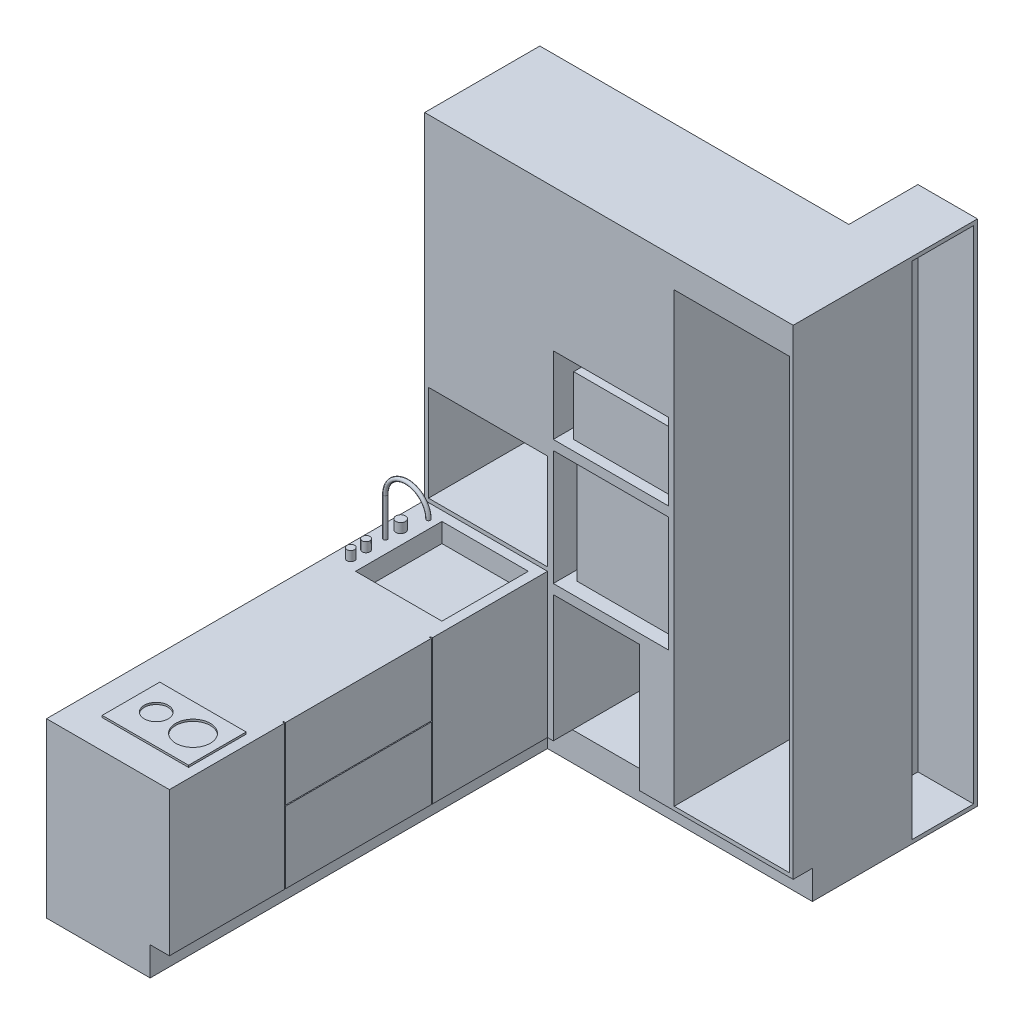
SolidWorks part; units mm, degrees
ref_plane "Спереди" through (0, 0, 0) normal (0, 0, 1) x (1, 0, 0)
ref_plane "Сверху" through (0, 0, 0) normal (0, 1, 0) x (1, 0, 0)
ref_plane "Справа" through (0, 0, 0) normal (1, 0, 0) x (0, 0, -1)
sketch "Эскиз1" plane through (0, 0, 0) normal (0, 1, 0) x (1, 0, 0)
  line L0 (-310, 0) -> (-1920, 0)
  line L1 (-1920, 0) -> (-1920, -2570)
  line L2 (-1920, -2570) -> (-1280, -2570)
  line L3 (-1280, -2570) -> (-1280, -600)
  line L4 (-1280, -600) -> (0, -600)
  line L5 (0, -600) -> (0, 0)
  line L6 (0, 0) -> (0, 360)
  line L7 (0, 360) -> (-310, 360)
  line L8 (-310, 360) -> (-310, 0)
  line L9 (0, 0) -> (-310, 0) construction
  dimension "D1" = 1610
  dimension "D2" = 2570
  dimension "D3" = 640
  dimension "D4" = 600
  dimension "D5" = 310
  dimension "D6" = 360
extrude "Бобышка-Вытянуть1" add sketch "Эскиз1" along normal blind 900
sketch "Эскиз2" plane through (0, 900, 0) normal (0, 1, 0) x (1, 0, 0)
  line L0 (-1920, 0) -> (-310, 0)
  line L1 (-310, 0) -> (-310, 360)
  line L2 (-310, 360) -> (0, 360)
  line L3 (0, 360) -> (0, -600)
  line L4 (0, -600) -> (-1920, -600)
  line L5 (-1920, 0) -> (-1920, -2570) construction
  line L6 (-1920, -600) -> (-1920, 0)
extrude "Бобышка-Вытянуть2" add sketch "Эскиз2" along normal blind 1750
sketch "Эскиз4" plane through (0, 0, 0) normal (0, -1, 0) x (-1, 0, 0)
  line L0 (1280, -2570) -> (1380, -2570)
  line L1 (1920, -2570) -> (1280, -2570) construction
  line L2 (1380, -2570) -> (1380, -500)
  line L3 (1380, -500) -> (0, -500)
  line L4 (0, -600) -> (0, 360) construction
  line L5 (0, -500) -> (0, -600)
  line L6 (0, -600) -> (1280, -600)
  line L7 (1280, -600) -> (1280, -2570)
  dimension "D1" = 100
extrude "Вырез-Вытянуть1" cut sketch "Эскиз4" against normal blind 150
sketch "Эскиз5" plane through (0, 0, 600) normal (0, 0, 1) x (1, 0, 0)
  line L0 (0, 150) -> (-1280, 150) construction
  line L1 (-620, 2500) -> (-20, 2500)
  line L2 (-620, 2500) -> (-620, 170)
  line L3 (-620, 170) -> (-20, 170)
  line L4 (-20, 2500) -> (-20, 170)
  line L5 (0, 2650) -> (0, 150) construction
  line L6 (-1920, 2650) -> (0, 2650) construction
  dimension "D1" = 20
  dimension "D2" = 20
  dimension "D3" = 150
  dimension "D4" = 600
extrude "Вырез-Вытянуть3" cut sketch "Эскиз5" against normal up to surface (600 mm away) up to face at (-1115, 1325, 0)
sketch "Эскиз6" plane through (0, 0, 600) normal (0, 0, 1) x (1, 0, 0)
  line L0 (-1380, 150) -> (0, 150) construction
  line L1 (-1250, 810) -> (-800, 810)
  line L2 (-1250, 810) -> (-1250, 150)
  line L3 (-1250, 150) -> (-800, 150)
  line L4 (-800, 810) -> (-800, 150)
  line L5 (-1280, 900) -> (-1280, 150) construction
  dimension "D1" = 450
  dimension "D2" = 660
  dimension "D3" = 30
extrude "Вырез-Вытянуть4" cut sketch "Эскиз6" against normal up to surface (600 mm away) up to face at (-790, 1330, 0)
sketch "Эскиз7" plane through (0, 0, 600) normal (0, 0, 1) x (1, 0, 0)
  line L0 (-1280, 900) -> (-1280, 150) construction
  line L1 (-1250, 1460) -> (-650, 1460)
  line L2 (-1250, 1460) -> (-1250, 860)
  line L3 (-1250, 860) -> (-650, 860)
  line L4 (-650, 1460) -> (-650, 860)
  line L5 (-800, 810) -> (-1250, 810) construction
  dimension "D1" = 600
  dimension "D2" = 600
  dimension "D3" = 30
  dimension "D4" = 50
extrude "Вырез-Вытянуть5" cut sketch "Эскиз7" against normal up to surface (600 mm away) up to face at (-1025, 480, 0)
sketch "Эскиз8" plane through (0, 0, 600) normal (0, 0, 1) x (1, 0, 0)
  line L0 (-1280, 900) -> (-1280, 150) construction
  line L1 (-1250, 1910) -> (-650, 1910)
  line L2 (-1250, 1910) -> (-1250, 1510)
  line L3 (-1250, 1510) -> (-650, 1510)
  line L4 (-650, 1910) -> (-650, 1510)
  line L5 (-650, 1460) -> (-1250, 1460) construction
  dimension "D1" = 600
  dimension "D2" = 400
  dimension "D3" = 30
  dimension "D4" = 50
extrude "Вырез-Вытянуть6" cut sketch "Эскиз8" against normal up to surface (600 mm away) up to face at (-950, 1160, 0)
sketch "Эскиз9" plane through (0, 0, 0) normal (1, 0, 0) x (0, 0, -1)
  line L0 (360, 2650) -> (360, 0) construction
  line L1 (340, 2630) -> (20, 2630)
  line L2 (340, 2630) -> (340, 20)
  line L3 (340, 20) -> (20, 20)
  line L4 (20, 2630) -> (20, 20)
  line L5 (-500, 0) -> (360, 0) construction
  line L6 (-600, 2650) -> (360, 2650) construction
  line L7 (0, 2500) -> (0, 170) construction
  dimension "D1" = 20
  dimension "D2" = 20
  dimension "D3" = 20
  dimension "D4" = 20
extrude "Вырез-Вытянуть7" cut sketch "Эскиз9" against normal offset from surface (290 mm away) 20 up to face at (-310, 1328.3333, -120)
sketch "Эскиз10" plane through (0, 900, 0) normal (0, 1, 0) x (1, 0, 0)
  line L0 (-1280, -2570) -> (-1280, -600) construction
  line L1 (-1780, -650) -> (-1330, -650)
  line L2 (-1780, -650) -> (-1780, -1100)
  line L3 (-1780, -1100) -> (-1330, -1100)
  line L4 (-1330, -650) -> (-1330, -1100)
  line L5 (-1920, -600) -> (-1280, -600) construction
  point P4 (-1330, -875)
  dimension "D1" = 450
  dimension "D2" = 450
  dimension "D3" = 50
  dimension "D4" = 50
extrude "Вырез-Вытянуть8" cut sketch "Эскиз10" against normal blind 100
sketch "Эскиз11" plane through (0, 0, 600) normal (0, 0, 1) x (1, 0, 0)
  line L0 (-1920, 900) -> (-1280, 900) construction
  line L1 (-1900, 1420) -> (-1280, 1420)
  line L2 (-1900, 1420) -> (-1900, 920)
  line L3 (-1900, 920) -> (-1280, 920)
  line L4 (-1280, 1420) -> (-1280, 920)
  line L5 (-1920, 2650) -> (-1920, 900) construction
  line L6 (-1280, 900) -> (-1280, 150) construction
  dimension "D1" = 20
  dimension "D2" = 20
  dimension "D3" = 500
extrude "Вырез-Вытянуть9" cut sketch "Эскиз11" against normal offset from surface (580 mm away) 20 up to face at (-950, 1710, 0)
sketch "Эскиз12" plane through (0, 900, 0) normal (0, 1, 0) x (1, 0, 0)
  line L0 (-1920, -2570) -> (-1280, -2570) construction
  line L1 (-1780, -2120) -> (-1330, -2120)
  line L2 (-1780, -2120) -> (-1780, -2420)
  line L3 (-1780, -2420) -> (-1330, -2420)
  line L4 (-1330, -2120) -> (-1330, -2420)
  line L5 (-1280, -2570) -> (-1280, -600) construction
  dimension "D1" = 450
  dimension "D2" = 300
  dimension "D3" = 150
  dimension "D4" = 50
extrude "Бобышка-Вытянуть3" add sketch "Эскиз12" along normal blind 10
sketch "Эскиз13" plane through (0, 910, 0) normal (0, 1, 0) x (1, 0, 0)
  circle A0 centre (-1654.208, -2264.2499) radius 62.0301
  circle A1 centre (-1462.547, -2264.2499) radius 90.2021
extrude "Вырез-Вытянуть10" cut sketch "Эскиз13" against normal blind 10
sketch "Эскиз14" plane through (-1280, 0, 0) normal (1, 0, 0) x (0, 0, -1)
  line L0 (-2570, 900) -> (-600, 900) construction
  line L1 (-1970, 900) -> (-1965, 900)
  line L2 (-1970, 900) -> (-1970, 150)
  line L3 (-1970, 150) -> (-1965, 150)
  line L4 (-1965, 522.5) -> (-1965, 150)
  line L5 (-2570, 150) -> (-500, 150) construction
  line L6 (-1965, 522.5) -> (-1205, 522.5)
  line L7 (-1205, 900) -> (-1200, 900)
  line L8 (-1205, 522.5) -> (-1205, 150)
  line L9 (-1205, 150) -> (-1200, 150)
  line L10 (-1200, 900) -> (-1200, 150)
  line L11 (-1965, 900) -> (-1965, 527.5)
  line L12 (-1965, 527.5) -> (-1205, 527.5)
  line L13 (-1205, 527.5) -> (-1205, 900)
  line L14 (-1205, 527.5) -> (-1205, 522.5) construction
  line L15 (-2570, 900) -> (-2570, 150) construction
  line L16 (-600, 900) -> (-600, 150) construction
  dimension "D1" = 5
  dimension "D2" = 600
  dimension "D3" = 600
  dimension "D4" = 760
extrude "Вырез-Вытянуть11" cut sketch "Эскиз14" against normal blind 10
sketch3d "Трехмерный эскиз1"
  line L0 (-1920, 900, 875) -> (-1850, 900, 875) construction
  line L1 (-1920, 900, 600) -> (-1920, 900, 2570) construction
  line L2 (-1850, 900, 875) -> (-1780, 900, 875) construction
  line L3 (-1780, 900, 650) -> (-1780, 900, 1100) construction
  line L4 (-1850, 900, 875) -> (-1850, 1100, 875)
  line L5 (-1850, 1100, 875) -> (-1737.5, 1100, 875) construction
  line L6 (-1737.5, 1100, 875) -> (-1625, 1100, 875) construction
  circle A0 centre (-1737.5, 1100, 875) radius 112.5 construction
  arc A1 (-1850, 1100, 875) -> (-1625, 1100, 875) centre (-1737.5, 1100, 875) cw
  point P9 (-1850, 1100, 875)
  point P11 (-1737.5, 1100, 987.5)
  point P12 (-1737.5, 1100, 762.5)
  point P14 (0, 0, 0)
  point P15 (0, 0, 0)
  point P16 (-1581.5622, 920, 600)
  point P17 (-1850, 1096.2096, 875)
  point P18 (-1625, 1100, 875)
  point P19 (-1625, 1100, 875)
  point P20 (-1737.5, 1100, 875)
  dimension "D1" = 225
  dimension "D2" = 200
sweep "По траектории1" add path "Трехмерный эскиз1" circular profile diameter 20 parameters "D3"=20
sketch "Эскиз21" plane through (0, 900, 0) normal (0, 1, 0) x (1, 0, 0)
  line L0 (-1850, -795) -> (-1850, -875) construction
  line L1 (-1850, -875) -> (-1850, -975) construction
  line L2 (-1850, -975) -> (-1850, -1055) construction
  circle A0 centre (-1850, -975) radius 20
  circle A1 centre (-1850, -1055) radius 20
  circle A2 centre (-1850, -795) radius 25
  point P6 (-1850, -875)
  point P8 (-1849.6293, -1024.1293)
  point P9 (-1850, -1057.2941)
  point P10 (-1850, -932.1162)
  point P12 (-1850, -979.8587)
  dimension "D2" = 40
  dimension "D4" = 50
  dimension "D1" = 100
  dimension "D3" = 80
  dimension "D5" = 80
extrude "Бобышка-Вытянуть4" add sketch "Эскиз21" along normal blind 50 contours A1
sketch "Эскиз22" plane through (0, 1510, 0) normal (0, 1, 0) x (1, 0, 0)
  line L1 (-1196.469, -288.5306) -> (-685.5454, -288.5306)
  line L2 (-1196.469, -288.5306) -> (-1196.469, -547.0437)
  line L3 (-1196.469, -547.0437) -> (-685.5454, -547.0437)
  line L4 (-685.5454, -288.5306) -> (-685.5454, -547.0437)
  point P4 (-1196.469, -521.8131)
  point P5 (-685.5454, -547.0437)
extrude "Бобышка-Вытянуть5" add sketch "Эскиз22" along normal blind 306
sketch "Эскиз23" plane through (0, 860, 0) normal (0, 1, 0) x (1, 0, 0)
  line L1 (-1198.5057, -98.9525) -> (-698.1039, -98.9525)
  line L2 (-1198.5057, -98.9525) -> (-1198.5057, -527.8866)
  line L3 (-1198.5057, -527.8866) -> (-698.1039, -527.8866)
  line L4 (-698.1039, -98.9525) -> (-698.1039, -527.8866)
  point P4 (-698.1039, -534.33)
  point P5 (-1214.427, -523.0246)
  point P6 (-1198.5057, -527.8866)
extrude "Бобышка-Вытянуть6" add sketch "Эскиз23" along normal blind 560
